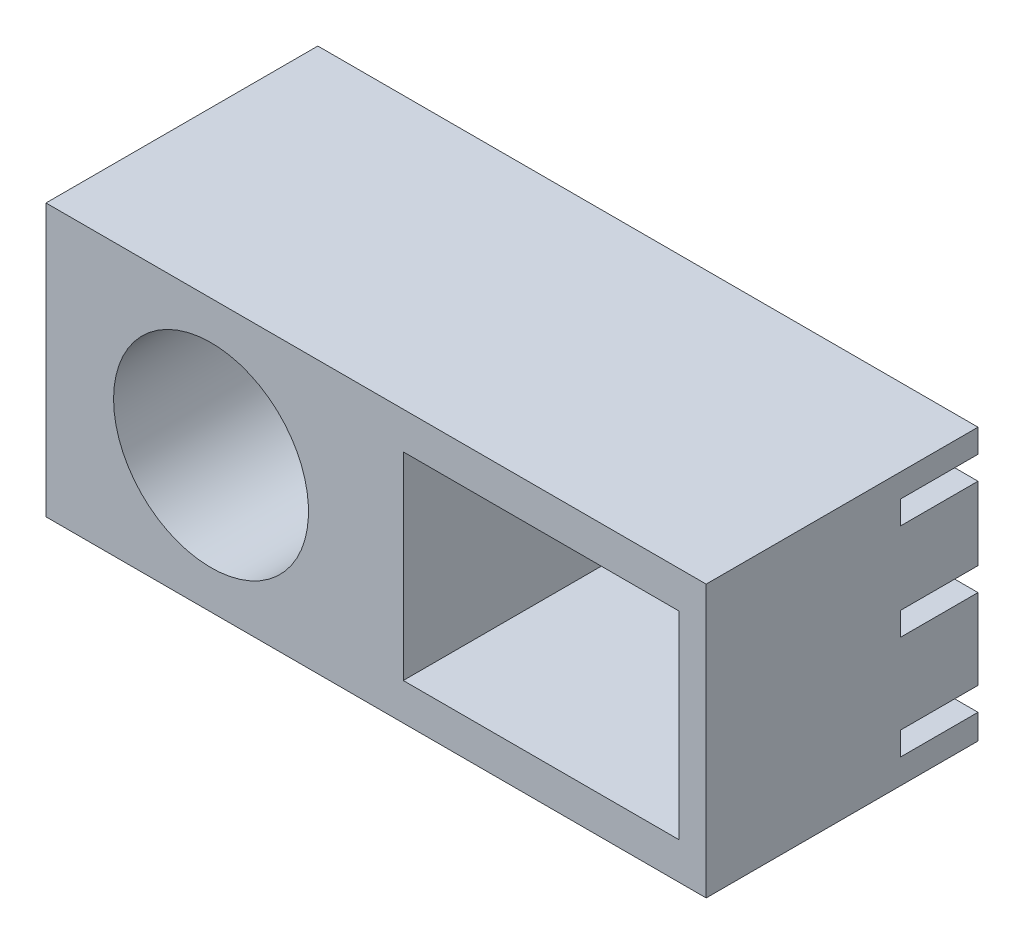
SolidWorks part; units mm, degrees
ref_plane "Alzado" through (0, 0, 0) normal (0, 0, 1) x (1, 0, 0)
ref_plane "Planta" through (0, 0, 0) normal (0, 1, 0) x (1, 0, 0)
ref_plane "Vista lateral" through (0, 0, 0) normal (1, 0, 0) x (0, 0, -1)
sketch "Croquis1" plane through (0, 0, 0) normal (0, 0, 1) x (1, 0, 0)
  line L1 (-3.3094, 6.7346) -> (13.6906, 6.7346)
  line L2 (-3.3094, 6.7346) -> (-3.3094, -0.2654)
  line L3 (-3.3094, -0.2654) -> (13.6906, -0.2654)
  line L4 (13.6906, 6.7346) -> (13.6906, -0.2654)
  line L5 (-3.3094, 6.7346) -> (13.6906, -0.2654) construction
  line L6 (-3.3094, -0.2654) -> (13.6906, 6.7346) construction
  point P4 (5.1906, 3.2346)
  dimension "D1" = 17
  dimension "D2" = 7
extrude "Saliente-Extruir1" add sketch "Croquis1" along normal blind 7
sketch "Croquis2" plane through (0, 0, 0) normal (0, 0, -1) x (-1, 0, 0)
  line L0 (-13.6906, 3.2346) -> (-5.1906, 3.2346) construction
  line L3 (-5.1906, 6.7346) -> (-5.1906, -0.2654) construction
  line L4 (-13.6906, 6.7346) -> (3.3094, 6.7346) construction
  line L5 (3.3094, -0.2654) -> (-13.6906, -0.2654) construction
  line L6 (-13.6906, -0.2654) -> (-13.6906, 6.7346) construction
  line L7 (-5.1906, 3.2346) -> (3.3094, 3.2346) construction
  line L8 (3.3094, 6.7346) -> (3.3094, -0.2654) construction
  line L10 (-12.9906, 0.6846) -> (-5.8906, 0.6846)
  line L11 (-12.9906, 0.6846) -> (-12.9906, 5.7846)
  line L12 (-12.9906, 5.7846) -> (-5.8906, 5.7846)
  line L13 (-5.8906, 0.6846) -> (-5.8906, 5.7846)
  line L14 (-12.9906, 0.6846) -> (-5.8906, 5.7846) construction
  line L15 (-12.9906, 5.7846) -> (-5.8906, 0.6846) construction
  circle A0 centre (-0.9406, 3.2346) radius 2.51
  point P15 (-9.4406, 3.2346)
  dimension "D1" = 7.1
  dimension "D2" = 5.1
extrude "Cortar-Extruir2" cut sketch "Croquis2" against normal blind 7 contours L11 L10 L13 L12 | A0
sketch "Croquis4" plane through (0, 0, 0) normal (0, 0, -1) x (-1, 0, 0)
  line L0 (-12.9906, 0.6846) -> (-12.9906, 5.7846) construction
  line L1 (-12.9906, 5.5293) -> (-13.6906, 5.5293)
  line L2 (-12.9906, 5.5293) -> (-12.9906, 6.1293)
  line L3 (-12.9906, 6.1293) -> (-13.6906, 6.1293)
  line L4 (-13.6906, 5.5293) -> (-13.6906, 6.1293)
  line L5 (-12.9906, 5.5293) -> (-13.6906, 6.1293) construction
  line L6 (-12.9906, 6.1293) -> (-13.6906, 5.5293) construction
  line L7 (-13.6906, -0.2654) -> (-13.6906, 6.7346) construction
  line L9 (-12.9906, 3.6461) -> (-13.6906, 3.6461)
  line L10 (-12.9906, 3.6461) -> (-12.9906, 3.0461)
  line L11 (-12.9906, 3.0461) -> (-13.6906, 3.0461)
  line L12 (-13.6906, 3.6461) -> (-13.6906, 3.0461)
  line L13 (-12.9906, 3.6461) -> (-13.6906, 3.0461) construction
  line L14 (-12.9906, 3.0461) -> (-13.6906, 3.6461) construction
  line L15 (-12.9906, 0.9761) -> (-13.6906, 0.9761)
  line L16 (-12.9906, 0.9761) -> (-12.9906, 0.3761)
  line L17 (-12.9906, 0.3761) -> (-13.6906, 0.3761)
  line L18 (-13.6906, 0.9761) -> (-13.6906, 0.3761)
  line L19 (-12.9906, 0.9761) -> (-13.6906, 0.3761) construction
  line L20 (-12.9906, 0.3761) -> (-13.6906, 0.9761) construction
  point P4 (-13.3406, 5.8293)
  point P13 (-13.3406, 3.3461)
  point P18 (-13.3406, 0.6761)
  dimension "D1" = 0.6
  dimension "D2" = 0.6
  dimension "D3" = 0.6
extrude "Cortar-Extruir3" cut sketch "Croquis4" against normal blind 2
sketch "Croquis5" plane through (0, 0, 0) normal (0, 0, -1) x (-1, 0, 0)
  line L0 (-12.9906, 5.7846) -> (-5.8906, 5.7846) construction
  line L1 (-12.9906, 6.1293) -> (-12.4906, 6.1293)
  line L2 (-12.9906, 6.1293) -> (-12.9906, 5.7846)
  line L3 (-12.9906, 5.7846) -> (-12.4906, 5.7846)
  line L4 (-12.4906, 6.1293) -> (-12.4906, 5.7846)
  line L5 (-12.9906, 6.1293) -> (-12.4906, 5.7846) construction
  line L6 (-12.9906, 5.7846) -> (-12.4906, 6.1293) construction
  line L7 (-12.9906, 0.6846) -> (-5.8906, 0.6846) construction
  line L8 (-12.9906, 0.3761) -> (-12.4906, 0.3761)
  line L9 (-12.9906, 0.3761) -> (-12.9906, 0.6846)
  line L10 (-12.9906, 0.6846) -> (-12.4906, 0.6846)
  line L11 (-12.4906, 0.3761) -> (-12.4906, 0.6846)
  line L12 (-12.9906, 0.3761) -> (-12.4906, 0.6846) construction
  line L13 (-12.9906, 0.6846) -> (-12.4906, 0.3761) construction
  point P4 (-12.7406, 5.957)
  point P12 (-12.7406, 0.5304)
  dimension "D1" = 0.5
extrude "Cortar-Extruir4" cut sketch "Croquis5" against normal blind 2
